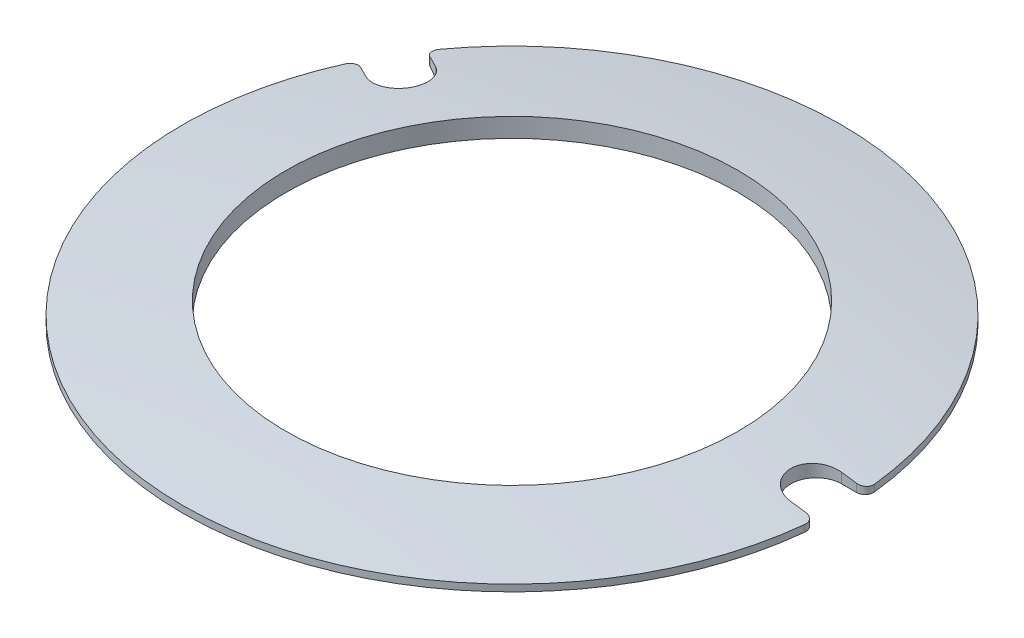
SolidWorks part; units mm, degrees
ref_plane "Front" through (0, 0, 0) normal (0, 0, 1) x (1, 0, 0)
ref_plane "Top" through (0, 0, 0) normal (0, 1, 0) x (1, 0, 0)
ref_plane "Right" through (0, 0, 0) normal (1, 0, 0) x (0, 0, -1)
sketch "Sketch1" plane through (0, 0, 0) normal (0, 0, 1) x (1, 0, 0)
  line L0 (0, 0) -> (0, 278.75) construction
  line L1 (39, 0) -> (39, 278.75) construction
  line L2 (39, 275.2083) -> (26.75, 275.2083)
  line L3 (0, 275.2083) -> (0, 278.75) construction
  line L4 (39, 276.0083) -> (39, 275.2083)
  line L5 (26.75, 277.4635) -> (26.75, 275.2083)
  line L7 (26.75, 275.2083) -> (0, 275.2083) construction
  arc A0 (39, 276.0083) -> (26.75, 277.4635) centre (0, 0) ccw
  arc A1 (26.75, 277.4635) -> (0, 278.75) centre (0, 0) ccw construction
  dimension "D3" = 0.8
  dimension "D1" = 278.75
  dimension "D4" = 26.75
  dimension "D2" = 39
revolve "Revolve1" add sketch "Sketch1" angle 360 about L0
sketch "Sketch2" plane through (0, 0, 0) normal (0, 1, 0) x (1, 0, 0)
  line L0 (36, 0) -> (46, 0) construction
  line L1 (36, 3) -> (46, 3)
  line L2 (36, -3) -> (46, -3)
  line L3 (-31.1769, 18) -> (-39.8372, 23) construction
  line L4 (-32.6769, 15.4019) -> (-41.3372, 20.4019)
  line L5 (-29.6769, 20.5981) -> (-38.3372, 25.5981)
  line L6 (0, 0) -> (36, 0) construction
  line L7 (0, 0) -> (-31.1769, 18) construction
  arc A2 (36, 3) -> (36, -3) centre (36, 0) ccw
  arc A3 (46, -3) -> (46, 3) centre (46, 0) ccw
  arc A4 (-32.6769, 15.4019) -> (-29.6769, 20.5981) centre (-31.1769, 18) ccw
  arc A5 (-38.3372, 25.5981) -> (-41.3372, 20.4019) centre (-39.8372, 23) ccw
  point P2 (41, 0)
  point P13 (-35.507, 20.5)
  dimension "D1" = 6
  dimension "D3" = 150
  dimension "D4" = 36
  dimension "D2" = 10
extrude "Cut-Extrude2" cut sketch "Sketch2" along normal through all
fillet "Fillet1" radius 1 4 edges at (-35.1749, 275.6083, -16.8441) (-32.1749, 275.6083, -22.0403) (38.8844, 275.6083, 3) (38.8844, 275.6083, -3)
